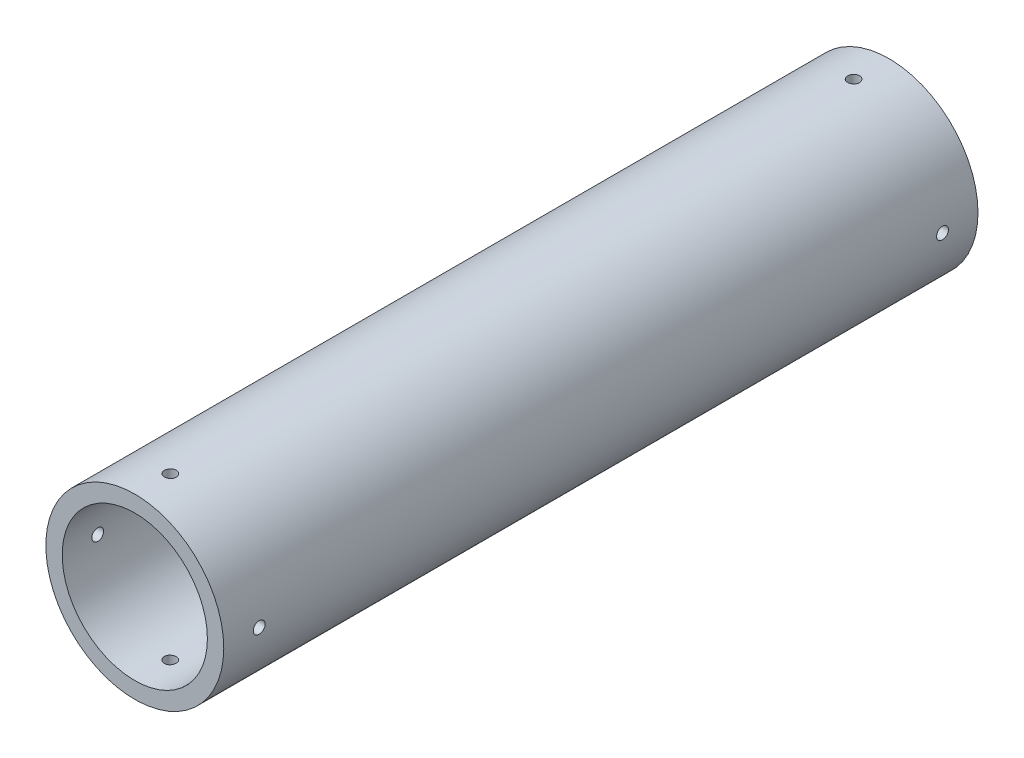
SolidWorks part; units mm, degrees
material "6061 Alloy"
ref_plane "Front Plane" through (0, 0, 0) normal (0, 0, 1) x (1, 0, 0)
ref_plane "Top Plane" through (0, 0, 0) normal (0, 1, 0) x (1, 0, 0)
ref_plane "Right Plane" through (0, 0, 0) normal (1, 0, 0) x (0, 0, -1)
sketch "Sketch1" plane through (0, 0, 0) normal (0, 0, 1) x (1, 0, 0)
  circle A0 centre (0, 0) radius 24.5618
  circle A1 centre (0, 0) radius 30.099
  dimension "D1" = 49.1236
  dimension "D2" = 60.198
extrude "Boss-Extrude1" add sketch "Sketch1" along normal blind 255.2
ref_plane "Plane1" through (0, 0, 12) normal (0, 0, -1) x (-1, 0, 0)
hole_wizard "Ø4.0mm Dowel Hole1" positions "3DSketch1" profile "Sketch2" hole size "Ø4.0" standard "ISO"
sketch3d "3DSketch1"
  line L0 (-30.099, 0, 12) -> (30.099, 0, 12)
  line L2 (0, -30.099, 12) -> (0, 30.099, 12)
  point P0 (0, 30.099, 12)
  point P2 (30.099, 0, 12)
  point P4 (0, -30.099, 12)
  point P6 (-30.099, 0, 12)
  dimension "D1" = 0
sketch "Sketch2" plane through (0, 30.099, 12) normal (1, 0, 0) x (0, 0, 1)
  line L0 (0, 0) -> (0, 7.2017)
  line L1 (0, 7.2017) -> (2, 6)
  line L2 (2, 6) -> (2, 0)
  line L5 (2, 0) -> (0, 0)
  line L10 (0, 7.2017) -> (-2, 6) construction
  line L11 (0, -6.35) -> (0, 107.95) construction
  dimension "Hole Dia." = 4
  dimension "Hole Depth" = 6
  dimension "Drill Angle" = 118
ref_plane "Plane2" through (0, 0, 243.2) normal (0, 0, 1) x (1, 0, 0)
hole_wizard "Ø4.0mm Dowel Hole2" positions "3DSketch2" profile "Sketch3" hole size "Ø4.0" standard "ISO"
sketch3d "3DSketch2"
  line L0 (30.099, 0, 243.2) -> (-30.099, 0, 243.2)
  line L2 (0, -30.099, 243.2) -> (0, 30.099, 243.2)
  point P0 (0, -30.099, 243.2)
  point P2 (-30.099, 0, 243.2)
  point P4 (0, 30.099, 243.2)
  point P6 (30.099, 0, 243.2)
  dimension "D1" = 0
sketch "Sketch3" plane through (0, -30.099, 243.2) normal (1, 0, 0) x (0, 0, -1)
  line L0 (0, 0) -> (0, 7.2017)
  line L1 (0, 7.2017) -> (2, 6)
  line L2 (2, 6) -> (2, 0)
  line L5 (2, 0) -> (0, 0)
  line L10 (0, 7.2017) -> (-2, 6) construction
  line L11 (0, -6.35) -> (0, 107.95) construction
  dimension "Hole Dia." = 4
  dimension "Hole Depth" = 6
  dimension "Drill Angle" = 118
